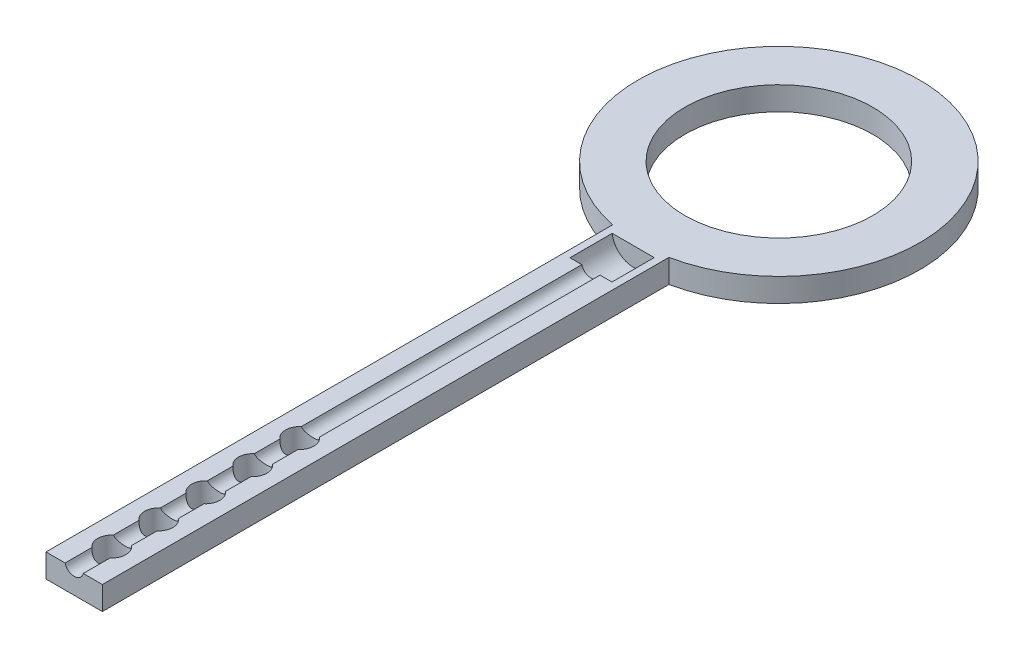
SolidWorks part; units mm, degrees
ref_plane "Front Plane" through (0, 0, 0) normal (0, 0, 1) x (1, 0, 0)
ref_plane "Top Plane" through (0, 0, 0) normal (0, 1, 0) x (1, 0, 0)
ref_plane "Right Plane" through (0, 0, 0) normal (1, 0, 0) x (0, 0, -1)
sketch "Sketch1" plane through (0, 0, 0) normal (0, 1, 0) x (1, 0, 0)
  line L3 (-6, -29.3939) -> (-6, -150)
  line L4 (-6, -150) -> (6, -150)
  line L5 (6, -150) -> (6, -29.3939)
  arc A1 (6, -29.3939) -> (-6, -29.3939) centre (0, 0) ccw
  circle A2 centre (0, 0) radius 20
  point P11 (0, -150)
  dimension "D1" = 40
  dimension "D2" = 30
  dimension "D5" = 12
  dimension "D6" = 150
extrude "Boss-Extrude1" add sketch "Sketch1" along normal blind 5
sketch "Sketch2" plane through (0, 5, 0) normal (0, 1, 0) x (1, 0, 0)
  circle A0 centre (0, -142) radius 3
  dimension "D1" = 6
  dimension "D2" = 142
extrude "Cut-Extrude1" cut sketch "Sketch2" against normal blind 10
pattern_linear "LPattern1" count 5 spacing 10 along (0, 0, -1) of "Cut-Extrude1"
sketch "Sketch3" plane through (0, 0, 150) normal (0, 0, 1) x (1, 0, 0)
  line L1 (-6, 5) -> (6, 5) construction
  circle A0 centre (0, 5.5) radius 2
  point P7 (0, 5)
  dimension "D1" = 4
  dimension "D2" = 0.5
extrude "Cut-Extrude2" cut sketch "Sketch3" against normal blind 116
sketch "Sketch4" plane through (0, 0, 150) normal (0, 0, 1) x (1, 0, 0)
  line L1 (-6, 5) -> (-1.9365, 5) construction
  line L2 (-1.9365, 5) -> (1.9365, 5) construction
  circle A0 centre (0, 5.5) radius 4.5
  point P8 (0, 5)
  dimension "D1" = 9
  dimension "D2" = 0.5
extrude "Cut-Extrude3" cut sketch "Sketch4" against normal blind 9 from offset 110 contours A0
